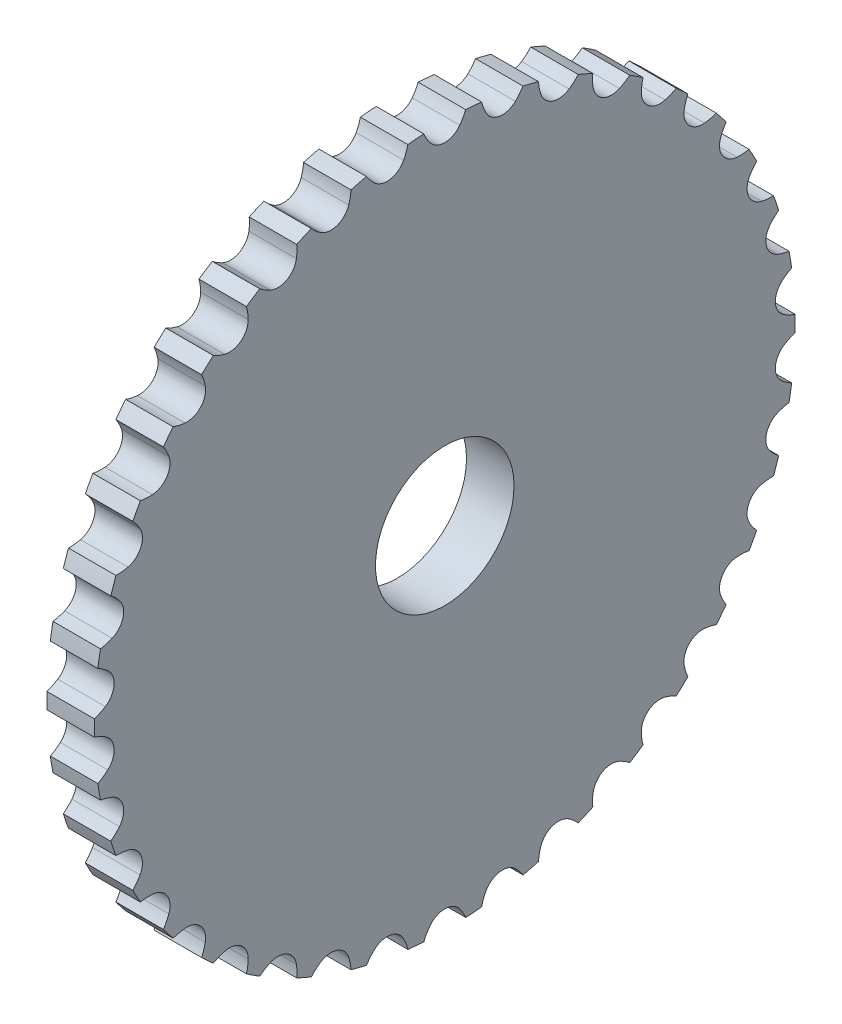
SolidWorks part; units mm, degrees
material "AISI 304"
ref_plane "Front Plane" through (0, 0, 0) normal (0, 0, 1) x (1, 0, 0)
ref_plane "Top Plane" through (0, 0, 0) normal (0, 1, 0) x (1, 0, 0)
ref_plane "Right Plane" through (0, 0, 0) normal (1, 0, 0) x (0, 0, -1)
sketch "Sketch1" plane through (0, 0, 0) normal (1, 0, 0) x (0, 0, -1)
  line L0 (0, 122.1167) -> (0, 0) construction
  line L1 (-48.9449, 96.1196) -> (51.9875, 96.1196) construction
  line L2 (6.527, 122.1167) -> (6.527, 0) construction
  line L3 (-48.9449, 100.9631) -> (51.9875, 100.9631) construction
  line L4 (6.527, 100.9631) -> (-8.0201, 90.1677) construction
  line L5 (6.527, 100.9631) -> (-5.8291, 96.1196) construction
  line L7 (-14.1757, 122.1167) -> (-14.1757, 0) construction
  line L8 (-48.9449, 94.9451) -> (51.9875, 94.9451) construction
  line L9 (0, 0) -> (-10.6805, 128.8948) construction
  line L10 (5.8291, 96.1196) -> (6.5046, 97.8428)
  line L11 (10.0712, 95.7681) -> (9.6886, 97.579)
  line L12 (21.5703, 93.8492) -> (22.5202, 95.4378)
  line L13 (25.6968, 92.8042) -> (25.6174, 94.6535)
  line L14 (36.7232, 89.0189) -> (37.9216, 90.4294)
  line L15 (40.6214, 87.309) -> (40.8474, 89.146)
  line L16 (50.8744, 81.7603) -> (52.2886, 82.9544)
  line L17 (54.4379, 79.4321) -> (54.9633, 81.2069)
  line L18 (63.6378, 72.2716) -> (65.2293, 73.2166)
  line L19 (66.7696, 69.3886) -> (67.5799, 71.0527)
  line L20 (74.6654, 60.8114) -> (76.3907, 61.4816)
  line L21 (77.2799, 57.4523) -> (78.3531, 58.9603)
  line L22 (83.6563, 47.6925) -> (85.4684, 48.0696)
  line L23 (85.6822, 43.9489) -> (86.989, 45.2597)
  line L24 (90.3652, 33.2727) -> (92.2147, 33.3463)
  line L25 (91.7474, 29.2466) -> (93.2521, 30.3245)
  line L26 (94.6093, 17.9453) -> (96.4456, 17.7135)
  line L27 (95.3099, 13.7466) -> (96.9715, 14.5621)
  line L28 (96.2726, 2.1283) -> (98.0458, 1.5975)
  line L29 (96.2726, -2.1283) -> (98.0458, -1.5975)
  line L30 (95.3099, -13.7466) -> (96.9715, -14.5621)
  line L31 (94.6093, -17.9453) -> (96.4456, -17.7135)
  line L32 (91.7474, -29.2466) -> (93.2521, -30.3245)
  line L33 (90.3652, -33.2727) -> (92.2147, -33.3463)
  line L34 (85.6822, -43.9489) -> (86.989, -45.2597)
  line L35 (83.6563, -47.6925) -> (85.4684, -48.0696)
  line L36 (77.2799, -57.4523) -> (78.3531, -58.9603)
  line L37 (74.6654, -60.8114) -> (76.3907, -61.4816)
  line L38 (66.7696, -69.3886) -> (67.5799, -71.0527)
  line L39 (63.6378, -72.2716) -> (65.2293, -73.2166)
  line L40 (54.4379, -79.4321) -> (54.9633, -81.2069)
  line L41 (50.8744, -81.7603) -> (52.2886, -82.9544)
  line L42 (40.6214, -87.309) -> (40.8474, -89.146)
  line L43 (36.7232, -89.0189) -> (37.9216, -90.4294)
  line L44 (25.6968, -92.8042) -> (25.6174, -94.6535)
  line L45 (21.5703, -93.8492) -> (22.5202, -95.4378)
  line L46 (10.0712, -95.7681) -> (9.6886, -97.579)
  line L47 (5.8291, -96.1196) -> (6.5046, -97.8428)
  line L48 (-5.8291, -96.1196) -> (-6.5046, -97.8428)
  line L49 (-10.0712, -95.7681) -> (-9.6886, -97.579)
  line L50 (-21.5703, -93.8492) -> (-22.5202, -95.4378)
  line L51 (-25.6968, -92.8042) -> (-25.6174, -94.6535)
  line L52 (-36.7232, -89.0189) -> (-37.9216, -90.4294)
  line L53 (-40.6214, -87.309) -> (-40.8474, -89.146)
  line L54 (-50.8744, -81.7603) -> (-52.2886, -82.9544)
  line L55 (-54.4379, -79.4321) -> (-54.9633, -81.2069)
  line L56 (-63.6378, -72.2716) -> (-65.2293, -73.2166)
  line L57 (-66.7696, -69.3886) -> (-67.5799, -71.0527)
  line L58 (-74.6654, -60.8114) -> (-76.3907, -61.4816)
  line L59 (-77.2799, -57.4523) -> (-78.3531, -58.9603)
  line L60 (-83.6563, -47.6925) -> (-85.4684, -48.0696)
  line L61 (-85.6822, -43.9489) -> (-86.989, -45.2597)
  line L62 (-90.3652, -33.2727) -> (-92.2147, -33.3463)
  line L63 (-91.7474, -29.2466) -> (-93.2521, -30.3245)
  line L64 (-94.6093, -17.9453) -> (-96.4456, -17.7135)
  line L65 (-95.3099, -13.7466) -> (-96.9715, -14.5621)
  line L66 (-96.2726, -2.1283) -> (-98.0458, -1.5975)
  line L67 (-96.2726, 2.1283) -> (-98.0458, 1.5975)
  line L68 (-95.3099, 13.7466) -> (-96.9715, 14.5621)
  line L69 (-94.6093, 17.9453) -> (-96.4456, 17.7135)
  line L70 (-91.7474, 29.2466) -> (-93.2521, 30.3245)
  line L71 (-90.3652, 33.2727) -> (-92.2147, 33.3463)
  line L72 (-85.6822, 43.9489) -> (-86.989, 45.2597)
  line L73 (-83.6563, 47.6925) -> (-85.4684, 48.0696)
  line L74 (-77.2799, 57.4523) -> (-78.3531, 58.9603)
  line L75 (-74.6654, 60.8114) -> (-76.3907, 61.4816)
  line L76 (-66.7696, 69.3886) -> (-67.5799, 71.0527)
  line L77 (-63.6378, 72.2716) -> (-65.2293, 73.2166)
  line L78 (-54.4379, 79.4321) -> (-54.9633, 81.2069)
  line L79 (-50.8744, 81.7603) -> (-52.2886, 82.9544)
  line L80 (-40.6214, 87.309) -> (-40.8474, 89.146)
  line L81 (-36.7232, 89.0189) -> (-37.9216, 90.4294)
  line L82 (-25.6968, 92.8042) -> (-25.6174, 94.6535)
  line L83 (-21.5703, 93.8492) -> (-22.5202, 95.4378)
  line L84 (-10.0712, 95.7681) -> (-9.6886, 97.579)
  line L85 (-6.5046, 97.8428) -> (-5.8291, 96.1196)
  circle A0 centre (0, 0) radius 96.1196
  arc A2 (-5.8291, 96.1196) -> (-4.112, 93.0679) centre (6.4947, 101.0449) ccw
  arc A4 (5.1188, 95.9832) -> (5.1206, 96.1196) centre (0, 96.1196) ccw
  arc A6 (-6.5046, 97.8428) -> (-8.3403, 100.6527) centre (-14.1757, 94.8358) ccw
  arc A7 (-4.112, 93.0679) -> (4.112, 93.0679) centre (0, 96.1196) ccw
  arc A8 (5.8291, 96.1196) -> (4.112, 93.0679) centre (-6.4947, 101.0449) cw
  arc A9 (6.5046, 97.8428) -> (8.3403, 100.6527) centre (14.1757, 94.8358) cw
  arc A10 (9.6886, 97.579) -> (8.3403, 100.6527) centre (1.6271, 95.8756) ccw
  arc A11 (10.0712, 95.7681) -> (11.2626, 92.4754) centre (23.0375, 98.5978) ccw
  arc A12 (11.2626, 92.4754) -> (19.3744, 91.1218) centre (15.8208, 94.8086) ccw
  arc A13 (21.5703, 93.8492) -> (19.3744, 91.1218) centre (10.2253, 100.7357) cw
  arc A14 (22.5202, 95.4378) -> (24.7935, 97.9072) centre (29.5919, 91.2091) cw
  arc A15 (25.6174, 94.6535) -> (24.7935, 97.9072) centre (17.3855, 94.3001) ccw
  arc A16 (25.6968, 92.8042) -> (26.3299, 89.3604) centre (38.952, 93.4612) ccw
  arc A17 (26.3299, 89.3604) -> (34.1083, 86.6901) centre (31.21, 90.9115) ccw
  arc A18 (36.7232, 89.0189) -> (34.1083, 86.6901) centre (26.6664, 97.6788) cw
  arc A19 (37.9216, 90.4294) -> (40.5703, 92.491) centre (44.2008, 85.0944) cw
  arc A20 (40.8474, 89.146) -> (40.5703, 92.491) centre (32.6696, 90.1525) ccw
  arc A21 (40.6214, 87.309) -> (40.6791, 83.8079) centre (53.8039, 85.7752) ccw
  arc A22 (40.6791, 83.8079) -> (47.9118, 79.8937) centre (45.7479, 84.5346) ccw
  arc A23 (50.8744, 81.7603) -> (47.9118, 79.8937) centre (42.3801, 91.9574) cw
  arc A24 (52.2886, 82.9544) -> (55.2405, 84.5519) centre (57.604, 76.6587) cw
  arc A25 (54.9633, 81.2069) -> (55.2405, 84.5519) centre (47.0627, 83.5457) ccw
  arc A26 (54.4379, 79.4321) -> (53.9186, 75.9693) centre (67.1882, 75.7495) ccw
  arc A27 (53.9186, 75.9693) -> (60.4084, 70.918) centre (59.0379, 75.8518) ccw
  arc A28 (63.6378, 72.2716) -> (60.4084, 70.918) centre (56.9378, 83.7277) cw
  arc A29 (65.2293, 73.2166) -> (68.4039, 74.3064) centre (69.436, 66.1318) cw
  arc A30 (67.5799, 71.0527) -> (68.4039, 74.3064) centre (60.172, 74.6599) ccw
  arc A31 (66.7696, 69.3886) -> (65.6873, 66.0585) centre (78.7398, 63.6575) ccw
  arc A32 (65.6873, 66.0585) -> (71.2573, 60.0079) centre (70.7175, 65.1) ccw
  arc A33 (74.6654, 60.8114) -> (71.2573, 60.0079) centre (69.9424, 73.2141) cw
  arc A34 (76.3907, 61.4816) -> (79.7014, 62.0341) centre (79.3739, 53.8011) cw
  arc A35 (78.3531, 58.9603) -> (79.7014, 62.0341) centre (71.6399, 63.7377) ccw
  arc A36 (77.2799, 57.4523) -> (75.6643, 54.3458) centre (88.1436, 49.8292) ccw
  arc A37 (75.6643, 54.3458) -> (80.1624, 47.4609) centre (80.4681, 52.5724) ccw
  arc A38 (83.6563, 47.6925) -> (80.1624, 47.4609) centre (81.0391, 60.7034) cw
  arc A39 (85.4684, 48.0696) -> (88.8248, 48.0696) centre (87.1467, 40.0028) cw
  arc A40 (86.989, 45.2597) -> (88.8248, 48.0696) centre (81.1537, 51.0769) ccw
  arc A41 (85.6822, 43.9489) -> (83.5774, 41.1506) centre (95.1431, 34.6416) ccw
  arc A42 (83.5774, 41.1506) -> (86.8809, 33.6193) centre (88.0237, 38.6108) ccw
  arc A43 (90.3652, 33.2727) -> (86.8809, 33.6193) centre (89.9253, 46.5369) cw
  arc A44 (92.2147, 33.3463) -> (95.5254, 32.7939) centre (92.5424, 25.1133) cw
  arc A45 (93.2521, 30.3245) -> (95.5254, 32.7939) centre (88.4539, 37.0228) ccw
  arc A46 (91.7474, 29.2466) -> (89.2106, 26.833) centre (99.5473, 18.5091) ccw
  arc A47 (89.2106, 26.833) -> (91.2295, 18.8607) centre (93.1783, 23.596) ccw
  arc A48 (94.6093, 17.9453) -> (91.2295, 18.8607) centre (96.3586, 31.101) cw
  arc A49 (96.4456, 17.7135) -> (99.6202, 16.6237) centre (95.4137, 9.5388) cw
  arc A50 (96.9715, 14.5621) -> (99.6202, 16.6237) centre (93.3412, 21.9588) ccw
  arc A51 (95.3099, 13.7466) -> (92.4105, 11.7834) centre (101.2361, 1.8717) ccw
  arc A52 (92.4105, 11.7834) -> (93.0896, 3.5875) centre (95.7913, 7.9375) ccw
  arc A53 (96.2726, 2.1283) -> (93.0896, 3.5875) centre (100.1634, 14.8167) cw
  arc A54 (98.0458, 1.5975) -> (100.9977, 0) centre (95.6825, -6.2958) cw
  arc A55 (98.0458, -1.5975) -> (100.9977, 0) centre (95.6825, 6.2958) ccw
  arc A56 (96.2726, -2.1283) -> (93.0896, -3.5875) centre (100.1634, -14.8167) ccw
  arc A57 (93.0896, -3.5875) -> (92.4105, -11.7834) centre (95.7913, -7.9375) ccw
  arc A58 (95.3099, -13.7466) -> (92.4105, -11.7834) centre (101.2361, -1.8717) cw
  arc A59 (96.9715, -14.5621) -> (99.6202, -16.6237) centre (93.3412, -21.9588) cw
  arc A60 (96.4456, -17.7135) -> (99.6202, -16.6237) centre (95.4137, -9.5388) ccw
  arc A61 (94.6093, -17.9453) -> (91.2295, -18.8607) centre (96.3586, -31.101) ccw
  arc A62 (91.2295, -18.8607) -> (89.2106, -26.833) centre (93.1783, -23.596) ccw
  arc A63 (91.7474, -29.2466) -> (89.2106, -26.833) centre (99.5473, -18.5091) cw
  arc A64 (93.2521, -30.3245) -> (95.5254, -32.7939) centre (88.4539, -37.0228) cw
  arc A65 (92.2147, -33.3463) -> (95.5254, -32.7939) centre (92.5424, -25.1133) ccw
  arc A66 (90.3652, -33.2727) -> (86.8809, -33.6193) centre (89.9253, -46.5369) ccw
  arc A67 (86.8809, -33.6193) -> (83.5774, -41.1506) centre (88.0237, -38.6108) ccw
  arc A68 (85.6822, -43.9489) -> (83.5774, -41.1506) centre (95.1431, -34.6416) cw
  arc A69 (86.989, -45.2597) -> (88.8248, -48.0696) centre (81.1537, -51.0769) cw
  arc A70 (85.4684, -48.0696) -> (88.8248, -48.0696) centre (87.1467, -40.0028) ccw
  arc A71 (83.6563, -47.6925) -> (80.1624, -47.4609) centre (81.0391, -60.7034) ccw
  arc A72 (80.1624, -47.4609) -> (75.6643, -54.3458) centre (80.4681, -52.5724) ccw
  arc A73 (77.2799, -57.4523) -> (75.6643, -54.3458) centre (88.1436, -49.8292) cw
  arc A74 (78.3531, -58.9603) -> (79.7014, -62.0341) centre (71.6399, -63.7377) cw
  arc A75 (76.3907, -61.4816) -> (79.7014, -62.0341) centre (79.3739, -53.8011) ccw
  arc A76 (74.6654, -60.8114) -> (71.2573, -60.0079) centre (69.9424, -73.2141) ccw
  arc A77 (71.2573, -60.0079) -> (65.6873, -66.0585) centre (70.7175, -65.1) ccw
  arc A78 (66.7696, -69.3886) -> (65.6873, -66.0585) centre (78.7398, -63.6575) cw
  arc A79 (67.5799, -71.0527) -> (68.4039, -74.3064) centre (60.172, -74.6599) cw
  arc A80 (65.2293, -73.2166) -> (68.4039, -74.3064) centre (69.436, -66.1318) ccw
  arc A81 (63.6378, -72.2716) -> (60.4084, -70.918) centre (56.9378, -83.7277) ccw
  arc A82 (60.4084, -70.918) -> (53.9186, -75.9693) centre (59.0379, -75.8518) ccw
  arc A83 (54.4379, -79.4321) -> (53.9186, -75.9693) centre (67.1882, -75.7495) cw
  arc A84 (54.9633, -81.2069) -> (55.2405, -84.5519) centre (47.0627, -83.5457) cw
  arc A85 (52.2886, -82.9544) -> (55.2405, -84.5519) centre (57.604, -76.6587) ccw
  arc A86 (50.8744, -81.7603) -> (47.9118, -79.8937) centre (42.3801, -91.9574) ccw
  arc A87 (47.9118, -79.8937) -> (40.6791, -83.8079) centre (45.7479, -84.5346) ccw
  arc A88 (40.6214, -87.309) -> (40.6791, -83.8079) centre (53.8039, -85.7752) cw
  arc A89 (40.8474, -89.146) -> (40.5703, -92.491) centre (32.6696, -90.1525) cw
  arc A90 (37.9216, -90.4294) -> (40.5703, -92.491) centre (44.2008, -85.0944) ccw
  arc A91 (36.7232, -89.0189) -> (34.1083, -86.6901) centre (26.6664, -97.6788) ccw
  arc A92 (34.1083, -86.6901) -> (26.3299, -89.3604) centre (31.21, -90.9115) ccw
  arc A93 (25.6968, -92.8042) -> (26.3299, -89.3604) centre (38.952, -93.4612) cw
  arc A94 (25.6174, -94.6535) -> (24.7935, -97.9072) centre (17.3855, -94.3001) cw
  arc A95 (22.5202, -95.4378) -> (24.7935, -97.9072) centre (29.5919, -91.2091) ccw
  arc A96 (21.5703, -93.8492) -> (19.3744, -91.1218) centre (10.2253, -100.7357) ccw
  arc A97 (19.3744, -91.1218) -> (11.2626, -92.4754) centre (15.8208, -94.8086) ccw
  arc A98 (10.0712, -95.7681) -> (11.2626, -92.4754) centre (23.0375, -98.5978) cw
  arc A99 (9.6886, -97.579) -> (8.3403, -100.6527) centre (1.6271, -95.8756) cw
  arc A100 (6.5046, -97.8428) -> (8.3403, -100.6527) centre (14.1757, -94.8358) ccw
  arc A101 (5.8291, -96.1196) -> (4.112, -93.0679) centre (-6.4947, -101.0449) ccw
  arc A102 (4.112, -93.0679) -> (-4.112, -93.0679) centre (0, -96.1196) ccw
  arc A103 (-5.8291, -96.1196) -> (-4.112, -93.0679) centre (6.4947, -101.0449) cw
  arc A104 (-6.5046, -97.8428) -> (-8.3403, -100.6527) centre (-14.1757, -94.8358) cw
  arc A105 (-9.6886, -97.579) -> (-8.3403, -100.6527) centre (-1.6271, -95.8756) ccw
  arc A106 (-10.0712, -95.7681) -> (-11.2626, -92.4754) centre (-23.0375, -98.5978) ccw
  arc A107 (-11.2626, -92.4754) -> (-19.3744, -91.1218) centre (-15.8208, -94.8086) ccw
  arc A108 (-21.5703, -93.8492) -> (-19.3744, -91.1218) centre (-10.2253, -100.7357) cw
  arc A109 (-22.5202, -95.4378) -> (-24.7935, -97.9072) centre (-29.5919, -91.2091) cw
  arc A110 (-25.6174, -94.6535) -> (-24.7935, -97.9072) centre (-17.3855, -94.3001) ccw
  arc A111 (-25.6968, -92.8042) -> (-26.3299, -89.3604) centre (-38.952, -93.4612) ccw
  arc A112 (-26.3299, -89.3604) -> (-34.1083, -86.6901) centre (-31.21, -90.9115) ccw
  arc A113 (-36.7232, -89.0189) -> (-34.1083, -86.6901) centre (-26.6664, -97.6788) cw
  arc A114 (-37.9216, -90.4294) -> (-40.5703, -92.491) centre (-44.2008, -85.0944) cw
  arc A115 (-40.8474, -89.146) -> (-40.5703, -92.491) centre (-32.6696, -90.1525) ccw
  arc A116 (-40.6214, -87.309) -> (-40.6791, -83.8079) centre (-53.8039, -85.7752) ccw
  arc A117 (-40.6791, -83.8079) -> (-47.9118, -79.8937) centre (-45.7479, -84.5346) ccw
  arc A118 (-50.8744, -81.7603) -> (-47.9118, -79.8937) centre (-42.3801, -91.9574) cw
  arc A119 (-52.2886, -82.9544) -> (-55.2405, -84.5519) centre (-57.604, -76.6587) cw
  arc A120 (-54.9633, -81.2069) -> (-55.2405, -84.5519) centre (-47.0627, -83.5457) ccw
  arc A121 (-54.4379, -79.4321) -> (-53.9186, -75.9693) centre (-67.1882, -75.7495) ccw
  arc A122 (-53.9186, -75.9693) -> (-60.4084, -70.918) centre (-59.0379, -75.8518) ccw
  arc A123 (-63.6378, -72.2716) -> (-60.4084, -70.918) centre (-56.9378, -83.7277) cw
  arc A124 (-65.2293, -73.2166) -> (-68.4039, -74.3064) centre (-69.436, -66.1318) cw
  arc A125 (-67.5799, -71.0527) -> (-68.4039, -74.3064) centre (-60.172, -74.6599) ccw
  arc A126 (-66.7696, -69.3886) -> (-65.6873, -66.0585) centre (-78.7398, -63.6575) ccw
  arc A127 (-65.6873, -66.0585) -> (-71.2573, -60.0079) centre (-70.7175, -65.1) ccw
  arc A128 (-74.6654, -60.8114) -> (-71.2573, -60.0079) centre (-69.9424, -73.2141) cw
  arc A129 (-76.3907, -61.4816) -> (-79.7014, -62.0341) centre (-79.3739, -53.8011) cw
  arc A130 (-78.3531, -58.9603) -> (-79.7014, -62.0341) centre (-71.6399, -63.7377) ccw
  arc A131 (-77.2799, -57.4523) -> (-75.6643, -54.3458) centre (-88.1436, -49.8292) ccw
  arc A132 (-75.6643, -54.3458) -> (-80.1624, -47.4609) centre (-80.4681, -52.5724) ccw
  arc A133 (-83.6563, -47.6925) -> (-80.1624, -47.4609) centre (-81.0391, -60.7034) cw
  arc A134 (-85.4684, -48.0696) -> (-88.8248, -48.0696) centre (-87.1467, -40.0028) cw
  arc A135 (-86.989, -45.2597) -> (-88.8248, -48.0696) centre (-81.1537, -51.0769) ccw
  arc A136 (-85.6822, -43.9489) -> (-83.5774, -41.1506) centre (-95.1431, -34.6416) ccw
  arc A137 (-83.5774, -41.1506) -> (-86.8809, -33.6193) centre (-88.0237, -38.6108) ccw
  arc A138 (-90.3652, -33.2727) -> (-86.8809, -33.6193) centre (-89.9253, -46.5369) cw
  arc A139 (-92.2147, -33.3463) -> (-95.5254, -32.7939) centre (-92.5424, -25.1133) cw
  arc A140 (-93.2521, -30.3245) -> (-95.5254, -32.7939) centre (-88.4539, -37.0228) ccw
  arc A141 (-91.7474, -29.2466) -> (-89.2106, -26.833) centre (-99.5473, -18.5091) ccw
  arc A142 (-89.2106, -26.833) -> (-91.2295, -18.8607) centre (-93.1783, -23.596) ccw
  arc A143 (-94.6093, -17.9453) -> (-91.2295, -18.8607) centre (-96.3586, -31.101) cw
  arc A144 (-96.4456, -17.7135) -> (-99.6202, -16.6237) centre (-95.4137, -9.5388) cw
  arc A145 (-96.9715, -14.5621) -> (-99.6202, -16.6237) centre (-93.3412, -21.9588) ccw
  arc A146 (-95.3099, -13.7466) -> (-92.4105, -11.7834) centre (-101.2361, -1.8717) ccw
  arc A147 (-92.4105, -11.7834) -> (-93.0896, -3.5875) centre (-95.7913, -7.9375) ccw
  arc A148 (-96.2726, -2.1283) -> (-93.0896, -3.5875) centre (-100.1634, -14.8167) cw
  arc A149 (-98.0458, -1.5975) -> (-100.9977, 0) centre (-95.6825, 6.2958) cw
  arc A150 (-98.0458, 1.5975) -> (-100.9977, 0) centre (-95.6825, -6.2958) ccw
  arc A151 (-96.2726, 2.1283) -> (-93.0896, 3.5875) centre (-100.1634, 14.8167) ccw
  arc A152 (-93.0896, 3.5875) -> (-92.4105, 11.7834) centre (-95.7913, 7.9375) ccw
  arc A153 (-95.3099, 13.7466) -> (-92.4105, 11.7834) centre (-101.2361, 1.8717) cw
  arc A154 (-96.9715, 14.5621) -> (-99.6202, 16.6237) centre (-93.3412, 21.9588) cw
  arc A155 (-96.4456, 17.7135) -> (-99.6202, 16.6237) centre (-95.4137, 9.5388) ccw
  arc A156 (-94.6093, 17.9453) -> (-91.2295, 18.8607) centre (-96.3586, 31.101) ccw
  arc A157 (-91.2295, 18.8607) -> (-89.2106, 26.833) centre (-93.1783, 23.596) ccw
  arc A158 (-91.7474, 29.2466) -> (-89.2106, 26.833) centre (-99.5473, 18.5091) cw
  arc A159 (-93.2521, 30.3245) -> (-95.5254, 32.7939) centre (-88.4539, 37.0228) cw
  arc A160 (-92.2147, 33.3463) -> (-95.5254, 32.7939) centre (-92.5424, 25.1133) ccw
  arc A161 (-90.3652, 33.2727) -> (-86.8809, 33.6193) centre (-89.9253, 46.5369) ccw
  arc A162 (-86.8809, 33.6193) -> (-83.5774, 41.1506) centre (-88.0237, 38.6108) ccw
  arc A163 (-85.6822, 43.9489) -> (-83.5774, 41.1506) centre (-95.1431, 34.6416) cw
  arc A164 (-86.989, 45.2597) -> (-88.8248, 48.0696) centre (-81.1537, 51.0769) cw
  arc A165 (-85.4684, 48.0696) -> (-88.8248, 48.0696) centre (-87.1467, 40.0028) ccw
  arc A166 (-83.6563, 47.6925) -> (-80.1624, 47.4609) centre (-81.0391, 60.7034) ccw
  arc A167 (-80.1624, 47.4609) -> (-75.6643, 54.3458) centre (-80.4681, 52.5724) ccw
  arc A168 (-77.2799, 57.4523) -> (-75.6643, 54.3458) centre (-88.1436, 49.8292) cw
  arc A169 (-78.3531, 58.9603) -> (-79.7014, 62.0341) centre (-71.6399, 63.7377) cw
  arc A170 (-76.3907, 61.4816) -> (-79.7014, 62.0341) centre (-79.3739, 53.8011) ccw
  arc A171 (-74.6654, 60.8114) -> (-71.2573, 60.0079) centre (-69.9424, 73.2141) ccw
  arc A172 (-71.2573, 60.0079) -> (-65.6873, 66.0585) centre (-70.7175, 65.1) ccw
  arc A173 (-66.7696, 69.3886) -> (-65.6873, 66.0585) centre (-78.7398, 63.6575) cw
  arc A174 (-67.5799, 71.0527) -> (-68.4039, 74.3064) centre (-60.172, 74.6599) cw
  arc A175 (-65.2293, 73.2166) -> (-68.4039, 74.3064) centre (-69.436, 66.1318) ccw
  arc A176 (-63.6378, 72.2716) -> (-60.4084, 70.918) centre (-56.9378, 83.7277) ccw
  arc A177 (-60.4084, 70.918) -> (-53.9186, 75.9693) centre (-59.0379, 75.8518) ccw
  arc A178 (-54.4379, 79.4321) -> (-53.9186, 75.9693) centre (-67.1882, 75.7495) cw
  arc A179 (-54.9633, 81.2069) -> (-55.2405, 84.5519) centre (-47.0627, 83.5457) cw
  arc A180 (-52.2886, 82.9544) -> (-55.2405, 84.5519) centre (-57.604, 76.6587) ccw
  arc A181 (-50.8744, 81.7603) -> (-47.9118, 79.8937) centre (-42.3801, 91.9574) ccw
  arc A182 (-47.9118, 79.8937) -> (-40.6791, 83.8079) centre (-45.7479, 84.5346) ccw
  arc A183 (-40.6214, 87.309) -> (-40.6791, 83.8079) centre (-53.8039, 85.7752) cw
  arc A184 (-40.8474, 89.146) -> (-40.5703, 92.491) centre (-32.6696, 90.1525) cw
  arc A185 (-37.9216, 90.4294) -> (-40.5703, 92.491) centre (-44.2008, 85.0944) ccw
  arc A186 (-36.7232, 89.0189) -> (-34.1083, 86.6901) centre (-26.6664, 97.6788) ccw
  arc A187 (-34.1083, 86.6901) -> (-26.3299, 89.3604) centre (-31.21, 90.9115) ccw
  arc A188 (-25.6968, 92.8042) -> (-26.3299, 89.3604) centre (-38.952, 93.4612) cw
  arc A189 (-25.6174, 94.6535) -> (-24.7935, 97.9072) centre (-17.3855, 94.3001) cw
  arc A190 (-22.5202, 95.4378) -> (-24.7935, 97.9072) centre (-29.5919, 91.2091) ccw
  arc A191 (-21.5703, 93.8492) -> (-19.3744, 91.1218) centre (-10.2253, 100.7357) ccw
  arc A192 (-19.3744, 91.1218) -> (-11.2626, 92.4754) centre (-15.8208, 94.8086) ccw
  arc A193 (-10.0712, 95.7681) -> (-11.2626, 92.4754) centre (-23.0375, 98.5978) cw
  arc A194 (-9.6886, 97.579) -> (-8.3403, 100.6527) centre (-1.6271, 95.8756) cw
  point P518 (0, 0)
  dimension "D1" = 192.2391
  dimension "D2" = 38
  dimension "D5" = 36.579
  dimension "D6" = 13.2715
  dimension "D7" = 15.174
  dimension "D12" = 4.737
  dimension "D3" = 6.527
  dimension "D4" = 4.8435
  dimension "D9" = 14.1757
  dimension "D10" = 1.1745
extrude "Boss-Extrude1" add sketch "Sketch1" along normal blind 13.031 contours A194 L84 A193 A192 A191 L83 A190 A189 L82 A188 A187 A186 L81 A185 A184 L80 A183 A182 A181 L79 A180 A179 L78 A178 A177 A176 L77 A175 A174 L76 A173 A172 A171 L75 A170 A169 L74 A168 A167 A166 L73 A165 A164 L72 A163 A162 A161 L71 A160 A159 L70
sketch "Sketch2" plane through (13.031, 0, 0) normal (1, 0, 0) x (0, 0, -1)
  line L0 (14.8998, 45.6289) -> (5.8978, 18.0614) construction
  circle A0 centre (0, 0) radius 19
  point P15 (0, 0)
  dimension "D1" = 38
extrude "Cut-Extrude1" cut sketch "Sketch2" against normal through all contours A0
